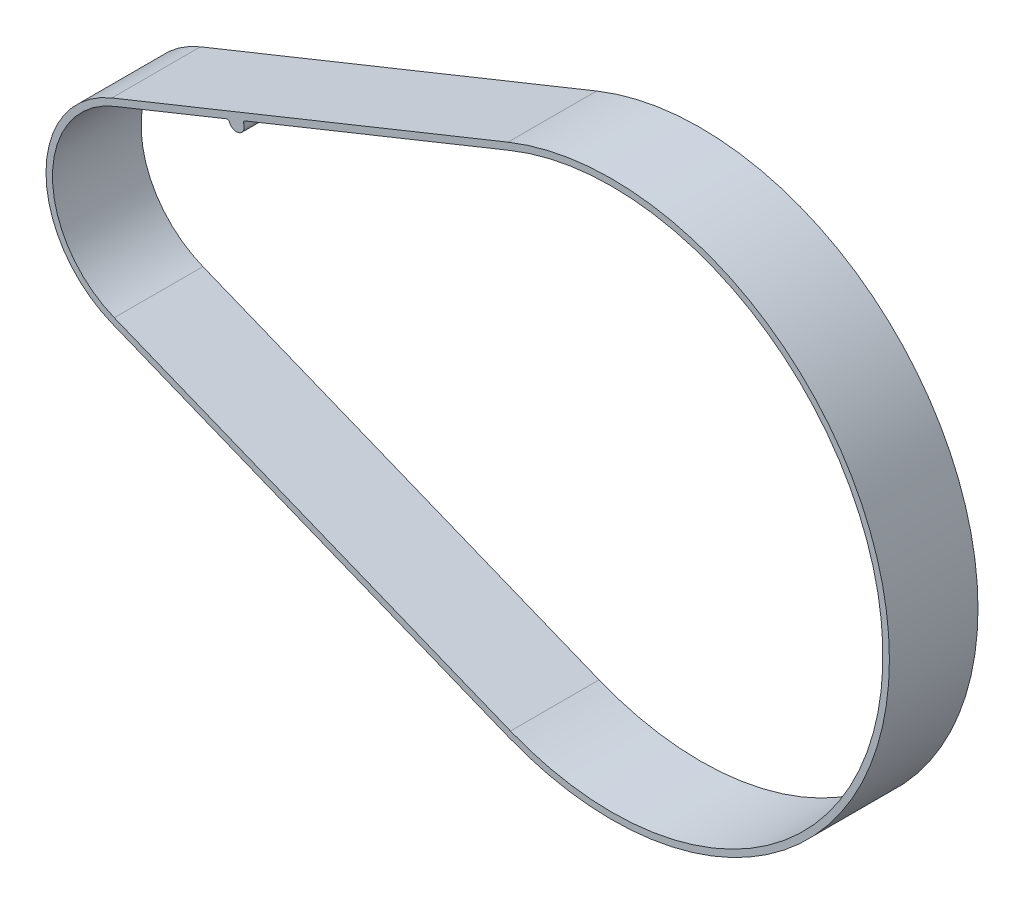
SolidWorks part; units mm, degrees
ref_plane "Front Plane" through (0, 0, 0) normal (0, 0, 1) x (1, 0, 0)
ref_plane "Top Plane" through (0, 0, 0) normal (0, 1, 0) x (1, 0, 0)
ref_plane "Right Plane" through (0, 0, 0) normal (1, 0, 0) x (0, 0, -1)
sketch "Sketch1" plane through (0, 0, 0) normal (0, 0, 1) x (1, 0, 0)
  line L0 (0, 0) -> (156, 0) construction
  line L1 (0, 0) -> (-33.4287, 0) construction
  line L2 (0, 0) -> (-32.4573, 8) construction
  line L3 (156, 0) -> (247.7897, 0) construction
  line L4 (156, 0) -> (247.4404, 8) construction
  line L5 (-12.506, 31.0012) -> (121.6606, 85.1244)
  line L6 (-12.506, -31.0012) -> (121.6606, -85.1244)
  line L9 (-13.329, 33.0415) -> (120.8376, 87.1646)
  line L10 (-13.329, -33.0415) -> (120.8376, -87.1646)
  line L11 (-11.234, 27.8481) -> (122.9326, 81.9713) construction
  line L12 (-11.234, -27.8481) -> (122.9326, -81.9713) construction
  line L16 (14.3061, 41.8211) -> (13.8808, 41.6457) construction
  arc A0 (-12.506, 31.0012) -> (-12.506, -31.0012) centre (0, 0) ccw
  arc A1 (121.6606, -85.1244) -> (121.6606, 85.1244) centre (156, 0) ccw
  arc A4 (120.8376, -87.1646) -> (120.8376, 87.1646) centre (156, 0) ccw
  arc A5 (-13.329, 33.0415) -> (-13.329, -33.0415) centre (0, 0) ccw
  arc A6 (122.9326, -81.9713) -> (122.9326, 81.9713) centre (156, 0) ccw construction
  arc A7 (-11.234, 27.8481) -> (-11.234, -27.8481) centre (0, 0) ccw construction
  point P23 (0, 0)
  point P26 (14.608, 41.0726)
  point P33 (14.3061, 41.8211)
  dimension "D6" = 3.4
  dimension "D1" = 156
  dimension "D2" = 13.846
  dimension "D3" = 8
  dimension "D4" = 5
  dimension "D5" = 8
  dimension "D7" = 2.2
extrude "Boss-Extrude1" add sketch "Sketch1" along normal mid plane 30 contours L9 A5 L10 A4 A1 L6 A0 L5
sketch "Sketch2" plane through (0, 0, 0) normal (0, 0, 1) x (1, 0, 0)
  line L3 (26.4252, 46.0226) -> (26.1793, 46.6069)
  line L4 (31.2377, 47.964) -> (30.9629, 48.5367)
  line L5 (30.9629, 48.5367) -> (26.1793, 46.6069)
  line L8 (29.8663, 44.4281) -> (28.8936, 46.8393) construction
  line L9 (26.8808, 44.8932) -> (25.051, 49.3634) construction
  line L10 (-11.234, -27.8481) -> (122.9326, -81.9713)
  line L11 (122.9326, 81.9713) -> (-11.234, 27.8481)
  line L12 (-11.234, -27.8481) -> (122.9326, -81.9713) construction
  line L13 (122.9326, 81.9713) -> (-11.234, 27.8481) construction
  line L14 (26.1793, 46.6069) -> (25.7527, 46.4349) construction
  line L15 (-12.506, 31.0012) -> (121.6606, 85.1244) construction
  line L16 (26.1793, 46.6069) -> (26.4252, 46.0226) construction
  arc A6 (26.4252, 46.0226) -> (31.2377, 47.964) centre (28.8936, 46.8393) ccw
  arc A8 (122.9326, -81.9713) -> (122.9326, 81.9713) centre (156, 0) ccw
  arc A9 (-11.234, 27.8481) -> (-11.234, -27.8481) centre (0, 0) ccw
  arc A10 (122.9326, -81.9713) -> (122.9326, 81.9713) centre (156, 0) ccw construction
  arc A11 (-11.234, 27.8481) -> (-11.234, -27.8481) centre (0, 0) ccw construction
  dimension "D1" = 3.4
extrude "Boss-Extrude2" add sketch "Sketch2" along normal mid plane 30
fillet "Fillet4" radius 0.8 2 edges at (30.9629, 48.5367, 0) (26.1793, 46.6069, 0)
